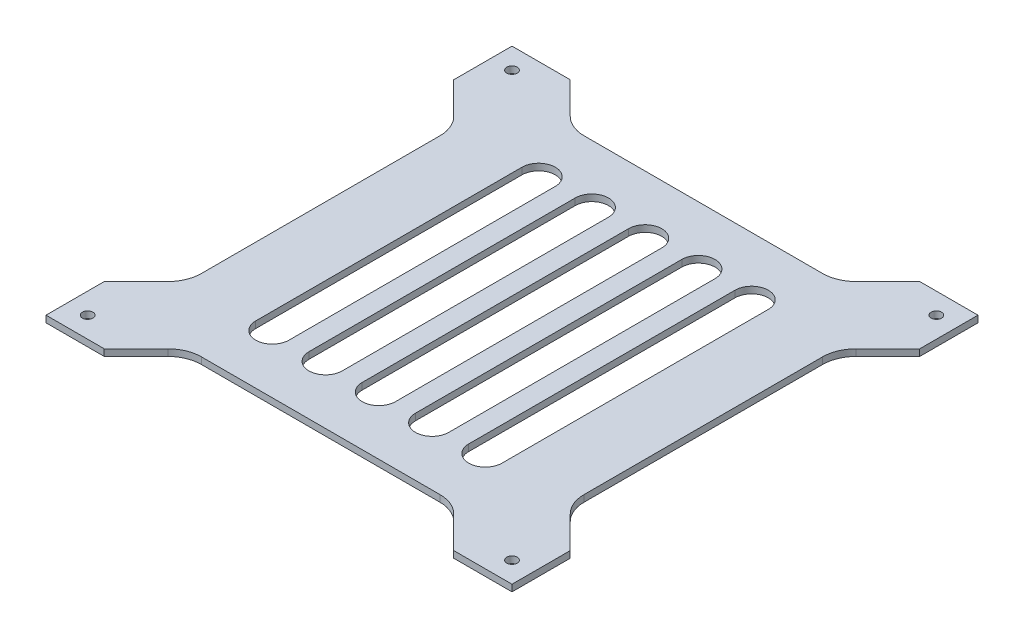
SolidWorks part; units mm, degrees
ref_plane "前视基准面" through (0, 0, 0) normal (0, 0, 1) x (1, 0, 0)
ref_plane "上视基准面" through (0, 0, 0) normal (0, 1, 0) x (1, 0, 0)
ref_plane "右视基准面" through (0, 0, 0) normal (1, 0, 0) x (0, 0, -1)
sketch "草图1" plane through (0, 0, 0) normal (0, 1, 0) x (1, 0, 0)
  line L0 (-52.5, 70) -> (-40, 57.5)
  line L1 (-70, -70) -> (-52.5, -70)
  line L2 (-70, -70) -> (-70, -52.5)
  line L3 (-70, 70) -> (-52.5, 70)
  line L4 (70, -70) -> (70, -52.5)
  line L5 (-70, -70) -> (70, 70) construction
  line L6 (-70, 70) -> (70, -70) construction
  line L7 (-40, 57.5) -> (40, 57.5)
  line L8 (0, 57.5) -> (0, 0) construction
  line L9 (52.5, 70) -> (40, 57.5)
  line L10 (-70, 0) -> (70, 0) construction
  line L11 (-52.5, -70) -> (-40, -57.5)
  line L12 (-40, -57.5) -> (40, -57.5)
  line L13 (52.5, -70) -> (40, -57.5)
  line L14 (70, -52.5) -> (57.5, -40)
  line L15 (57.5, 40) -> (57.5, -40)
  line L16 (70, 52.5) -> (57.5, 40)
  line L17 (-70, -52.5) -> (-57.5, -40)
  line L18 (-57.5, 40) -> (-57.5, -40)
  line L19 (-70, 52.5) -> (-57.5, 40)
  line L20 (52.5, 70) -> (70, 70)
  line L21 (-70, 52.5) -> (-70, 70)
  line L22 (70, 52.5) -> (70, 70)
  line L23 (52.5, -70) -> (70, -70)
  circle A0 centre (-63.7413, 63.7413) radius 1.569
  circle A1 centre (63.7413, 63.7413) radius 1.569
  circle A2 centre (63.7413, -63.7413) radius 1.569
  circle A3 centre (-63.7413, -63.7413) radius 1.569
  point P8 (0, 0)
  point P37 (0, 0)
  dimension "D1" = 140
  dimension "D2" = 140
  dimension "D3" = 12.5
  dimension "D4" = 40
  dimension "D5" = 135
  dimension "D6" = 2
extrude "凸台-拉伸1" add sketch "草图1" along normal blind 2
fillet "圆角1" radius 10 8 edges at (57.5, 1, 40) (-57.5, 1, -40) (-57.5, 1, 40) (-40, 1, 57.5) (40, 1, 57.5) (57.5, 1, -40) (40, 1, -57.5) (-40, 1, -57.5)
sketch "草图2" plane through (0, 2, 0) normal (0, 1, 0) x (1, 0, 0)
  line L0 (0, -40) -> (0, 40) construction
  line L1 (-5, -40) -> (-5, 40)
  line L2 (5, -40) -> (5, 40)
  line L3 (16, -40) -> (16, 40) construction
  line L4 (11, -40) -> (11, 40)
  line L5 (21, -40) -> (21, 40)
  line L6 (32, -40) -> (32, 40) construction
  line L7 (27, -40) -> (27, 40)
  line L8 (37, -40) -> (37, 40)
  line L9 (-16, -40) -> (-16, 40) construction
  line L10 (-21, -40) -> (-21, 40)
  line L11 (-11, -40) -> (-11, 40)
  line L12 (-32, -40) -> (-32, 40) construction
  line L13 (-37, -40) -> (-37, 40)
  line L14 (-27, -40) -> (-27, 40)
  arc A0 (-5, -40) -> (5, -40) centre (0, -40) ccw
  arc A1 (5, 40) -> (-5, 40) centre (0, 40) ccw
  arc A2 (11, -40) -> (21, -40) centre (16, -40) ccw
  arc A3 (21, 40) -> (11, 40) centre (16, 40) ccw
  arc A4 (27, -40) -> (37, -40) centre (32, -40) ccw
  arc A5 (37, 40) -> (27, 40) centre (32, 40) ccw
  arc A6 (-21, -40) -> (-11, -40) centre (-16, -40) ccw
  arc A7 (-11, 40) -> (-21, 40) centre (-16, 40) ccw
  arc A8 (-37, -40) -> (-27, -40) centre (-32, -40) ccw
  arc A9 (-27, 40) -> (-37, 40) centre (-32, 40) ccw
  point P2 (0, 0)
  point P11 (16, 0)
  point P18 (32, 0)
  point P25 (-16, 0)
  point P32 (-32, 0)
  dimension "D2" = 5
  dimension "D1" = 80
  dimension "D3" = 3
  dimension "D4" = 3
extrude "切除-拉伸1" cut sketch "草图2" against normal blind 2
